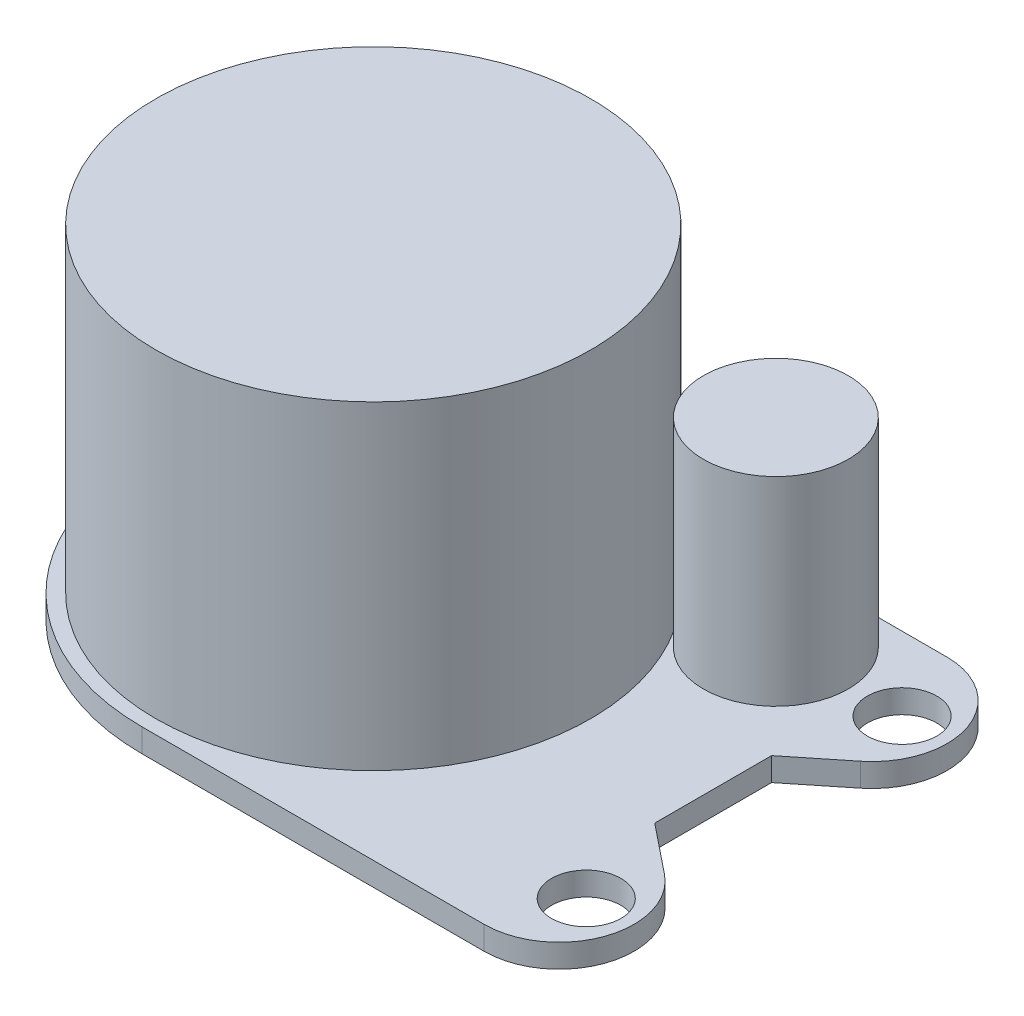
SolidWorks part; units mm, degrees
ref_plane "Front Plane" through (0, 0, 0) normal (0, 0, 1) x (1, 0, 0)
ref_plane "Top Plane" through (0, 0, 0) normal (0, 1, 0) x (1, 0, 0)
ref_plane "Right Plane" through (0, 0, 0) normal (1, 0, 0) x (0, 0, -1)
sketch "Sketch1" plane through (0, 0, 0) normal (0, 1, 0) x (1, 0, 0)
  line L0 (-13.933, -3.0843) -> (-13.933, 10.3038) construction
  line L1 (-13.933, 13.5097) -> (-28.5771, 13.5097)
  line L2 (-14.0371, 1.1097) -> (-11.9265, -0.5839)
  line L3 (-28.5771, -6.2903) -> (-13.933, -6.2903)
  line L4 (-13.933, 3.6097) -> (-28.5771, 3.6097) construction
  line L5 (-14.0371, 6.1097) -> (-14.0371, 1.1097)
  line L6 (-14.0371, 6.1097) -> (-11.9265, 7.8034)
  line L7 (-38.4771, 3.6097) -> (-38.4771, 28.7573) construction
  line L8 (-10.7271, 10.3038) -> (-10.7271, 30.8829) construction
  arc A0 (-11.9265, 7.8034) -> (-13.933, 13.5097) centre (-13.933, 10.3038) ccw
  arc A1 (-13.933, -6.2903) -> (-11.9265, -0.5839) centre (-13.933, -3.0843) ccw
  arc A2 (-28.5771, 13.5097) -> (-28.5771, -6.2903) centre (-28.5771, 3.6097) ccw
  point P13 (-14.0371, 3.6097)
  dimension "D1" = 9.9
  dimension "D2" = 27.75
  dimension "D3" = 24.44
  dimension "D4" = 19.8
  dimension "D5" = 5
extrude "Boss-Extrude1" add sketch "Sketch1" along normal blind 1
sketch "Sketch2" plane through (0, 1, 0) normal (0, 1, 0) x (1, 0, 0)
  circle A0 centre (-28.5771, 3.6097) radius 9.305
  dimension "D1" = 18.61
extrude "Boss-Extrude2" add sketch "Sketch2" along normal blind 13.66
sketch "Sketch3" plane through (0, 1, 0) normal (0, 1, 0) x (1, 0, 0)
  line L0 (-13.933, 13.5097) -> (-28.5771, 13.5097) construction
  circle A0 centre (-17.9627, 10.2157) radius 3.1
  dimension "D1" = 6.2
  dimension "D2" = 3.294
extrude "Boss-Extrude3" add sketch "Sketch3" along normal blind 8.51
sketch "Sketch4" plane through (0, 1, 0) normal (0, 1, 0) x (1, 0, 0)
  line L0 (-12.7121, 10.3647) -> (-12.7121, -3.1453) construction
  line L1 (-12.7121, 3.6097) -> (-14.0371, 3.6097) construction
  line L2 (-11.2271, -3.1453) -> (-11.2271, 2.4395) construction
  line L3 (-10.7271, -3.0843) -> (-10.7271, 2.4395) construction
  line L4 (-14.0371, 1.1097) -> (-14.0371, 6.1097) construction
  circle A0 centre (-12.7121, 10.3647) radius 1.485
  circle A1 centre (-12.7121, -3.1453) radius 1.485
  arc A2 (-13.933, -6.2903) -> (-11.9265, -0.5839) centre (-13.933, -3.0843) ccw construction
  dimension "D1" = 2.97
  dimension "D2" = 0.5
  dimension "D3" = 13.51
extrude "Cut-Extrude1" cut sketch "Sketch4" against normal blind 8.51
